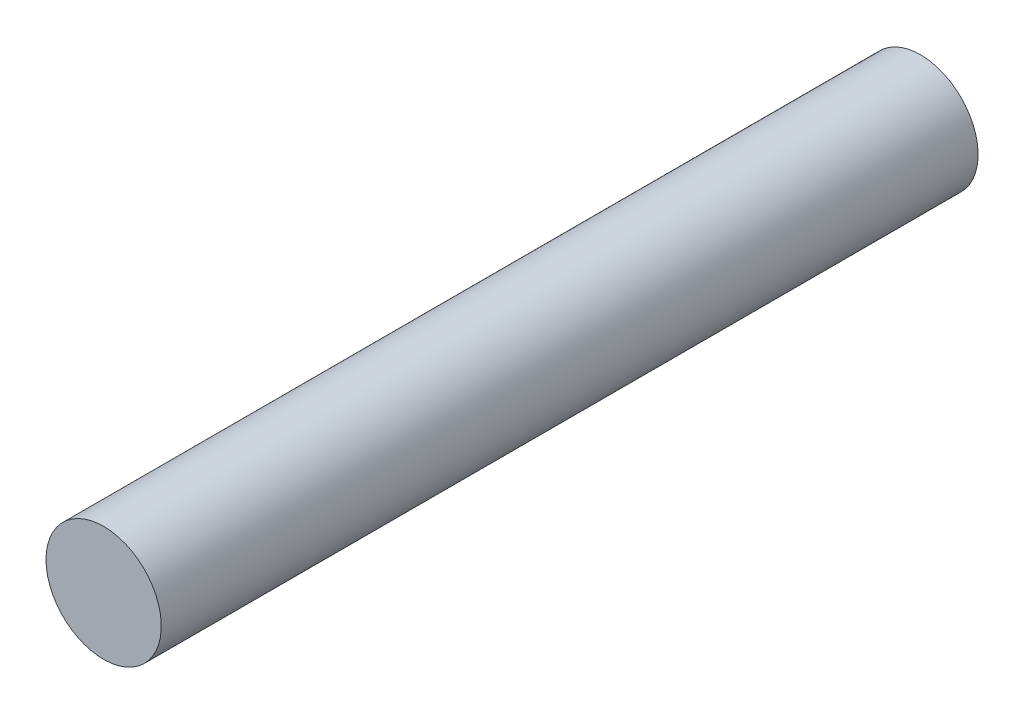
SolidWorks part; units mm, degrees
ref_plane "Front Plane" through (0, 0, 0) normal (0, 0, 1) x (1, 0, 0)
ref_plane "Top Plane" through (0, 0, 0) normal (0, 1, 0) x (1, 0, 0)
ref_plane "Right Plane" through (0, 0, 0) normal (1, 0, 0) x (0, 0, -1)
sketch "Sketch1" plane through (0, 0, 0) normal (0, 0, 1) x (1, 0, 0)
  circle A0 centre (0, 0) radius 12.7
  dimension "D1" = 25.4
extrude "Boss-Extrude1" add sketch "Sketch1" along normal blind 180
